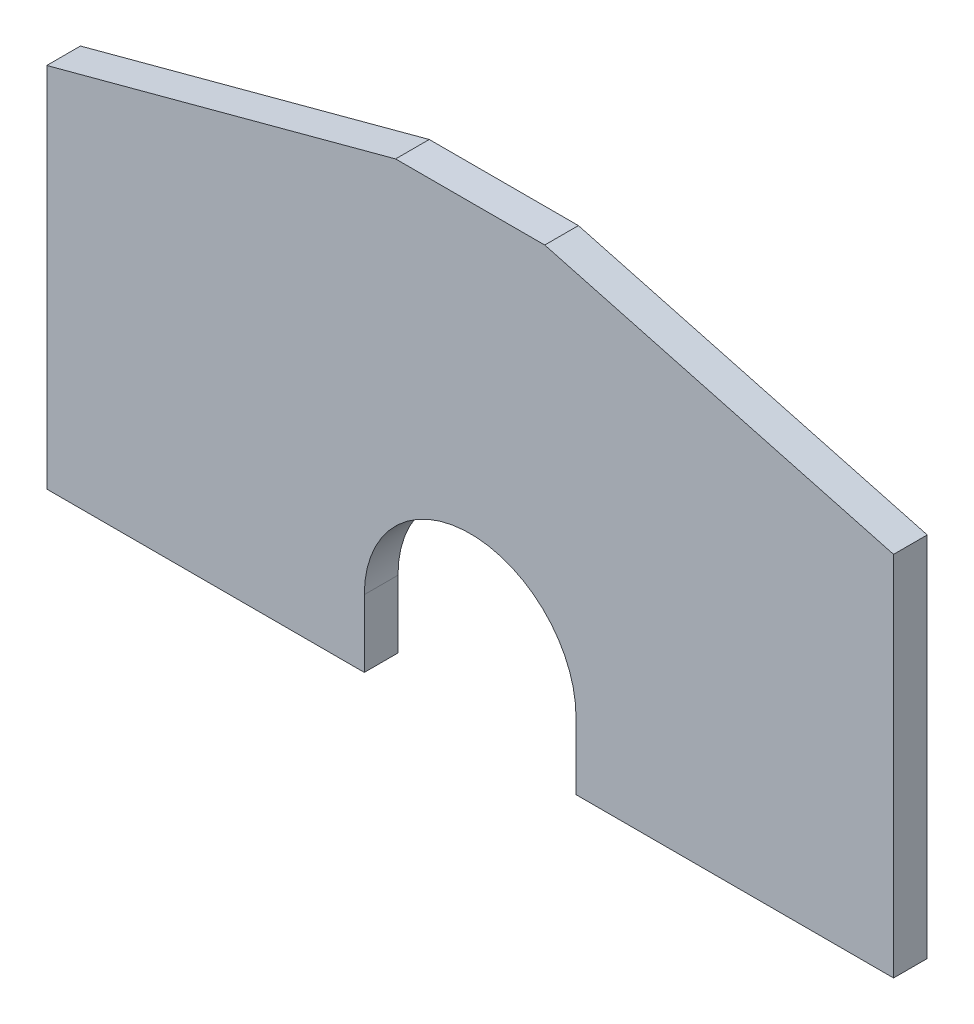
SolidWorks part; units mm, degrees
ref_plane "Ebene vorne" through (0, 0, 0) normal (0, 0, 1) x (1, 0, 0)
ref_plane "Ebene oben" through (0, 0, 0) normal (0, 1, 0) x (1, 0, 0)
ref_plane "Ebene rechts" through (0, 0, 0) normal (1, 0, 0) x (0, 0, -1)
sketch "Skizze1" plane through (0, 0, 0) normal (0, 0, 1) x (1, 0, 0)
  line L1 (62.8775, 389.0766) -> (62.8775, 7.8066)
  line L2 (62.8775, 7.8066) -> (-267.1225, 7.8066)
  line L3 (-267.1225, 7.8066) -> (-267.1225, 77.8066)
  line L4 (-817.1225, 389.0766) -> (-817.1225, 7.8066)
  line L5 (-817.1225, 7.8066) -> (-487.1225, 7.8066)
  line L6 (-487.1225, 7.8066) -> (-487.1225, 77.8066)
  line L7 (-817.1225, 389.0766) -> (-454.6225, 486.2082)
  line L8 (-454.6225, 486.2082) -> (-299.6225, 486.2082)
  line L9 (-299.6225, 486.2082) -> (62.8775, 389.0766)
  arc A0 (-487.1225, 77.8066) -> (-267.1225, 77.8066) centre (-377.1225, 77.8066) cw
  point P11 (0, 0)
  point P12 (-817.1225, 240.6497)
  point P13 (0, 0)
  dimension "D1" = 330
  dimension "D2" = 155
  dimension "D3" = 70
  dimension "D4" = 381.27
  dimension "D5" = 105
  dimension "D6" = 880
extrude "Aufsatz-Linear austragen1" add sketch "Skizze1" along normal blind 35
